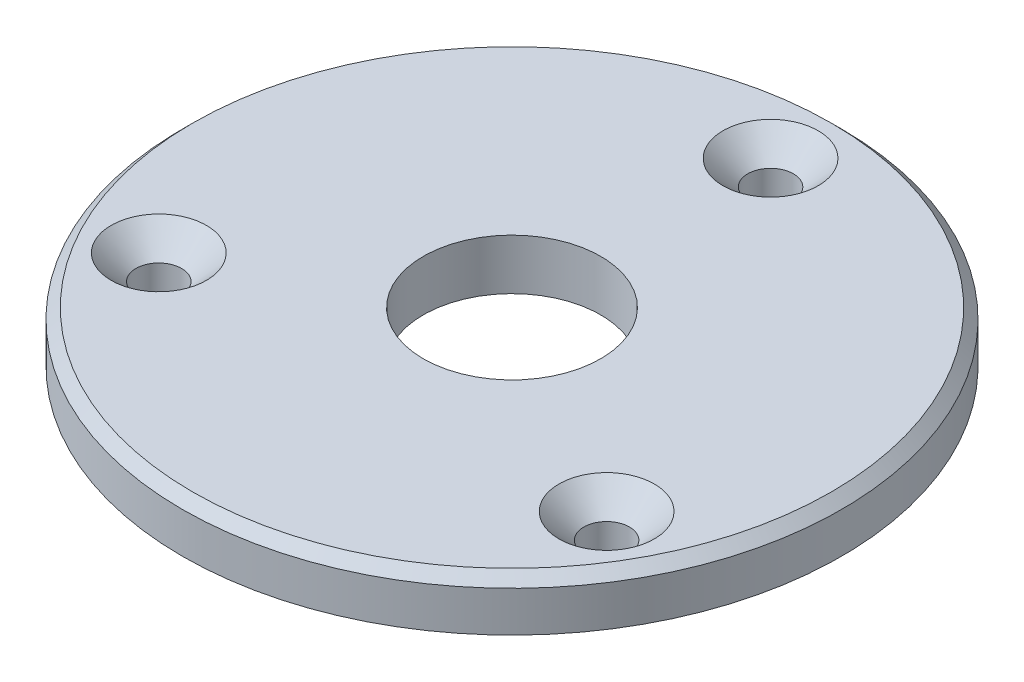
SolidWorks part; units mm, degrees
ref_plane "Front Plane" through (0, 0, 0) normal (0, 0, 1) x (1, 0, 0)
ref_plane "Top Plane" through (0, 0, 0) normal (0, 1, 0) x (1, 0, 0)
ref_plane "Right Plane" through (0, 0, 0) normal (1, 0, 0) x (0, 0, -1)
sketch "Sketch1" plane through (0, 0, 0) normal (0, 1, 0) x (1, 0, 0)
  circle A1 centre (0, 0) radius 32.5
  dimension "D1" = 65
extrude "Boss-Extrude1" add sketch "Sketch1" along normal blind 5
chamfer "Chamfer1" distance 1 angle 45 1 edges at (0, 5, 32.5)
sketch "Sketch2" plane through (0, 5, 0) normal (0, 1, 0) x (1, 0, 0)
  line L0 (0, 5.75) -> (0, 31.5) construction
  circle A2 centre (0, 0) radius 5.75
  circle A3 centre (0, 0) radius 31.5 construction
  point P7 (0, 25.5)
  dimension "D1" = 11.5
  dimension "D2" = 6
hole_wizard "CSK for M4 Countersunk Flat Head1" positions "3DSketch1" profile "Sketch3" countersink size "M4" standard "BSI" end condition through all
sketch3d "3DSketch1"
  point P0 (0, 5, -25.5)
sketch "Sketch3" plane through (0, 5, -25.5) normal (1, 0, 0) x (0, 0, 1)
  line L0 (0, 0) -> (0, 5)
  line L1 (0, 5) -> (2.25, 5)
  line L2 (2.25, 5) -> (2.25, 2.45)
  line L3 (2.25, 2.45) -> (4.7, 0)
  line L5 (4.7, 0) -> (0, 0)
  line L6 (-2.25, 2.45) -> (-4.7, 0) construction
  line L11 (0, -6.35) -> (0, 107.95) construction
  dimension "Thru Hole Dia." = 4.5
  dimension "Thru Hole Depth" = 5
  dimension "Near C'Sink Dia." = 9.4
  dimension "Near C'Sink Angle" = 90
hole_wizard "M20x2.5 Tapped Hole1" positions "3DSketch2" profile "Sketch4" tap size "M20x2.5" standard "BSI" end condition through all
sketch3d "3DSketch2"
  point P0 (0, 0, 0)
  point P3 (0, 5, 0)
cosmetic thread "Hole Thread1" parameters "D2"=20
cosmetic thread "Hole Thread2" parameters "D2"=20
sketch "Sketch4" plane through (0, 5, 0) normal (1, 0, 0) x (0, 0, 1)
  line L0 (0, 0) -> (0, 5)
  line L1 (0, 5) -> (8.75, 5)
  line L2 (8.75, 5) -> (8.75, 0)
  line L5 (8.75, 0) -> (0, 0)
  line L11 (0, -6.35) -> (0, 107.95) construction
  dimension "Thru Tap Drill Dia." = 17.5
  dimension "Thru Tap Drill Depth" = 5
pattern_circular "CirPattern1" count 3 over 360 about axis through (0, 0, 0) along (0, 1, 0) of "CSK for M4 Countersunk Flat Head1"
